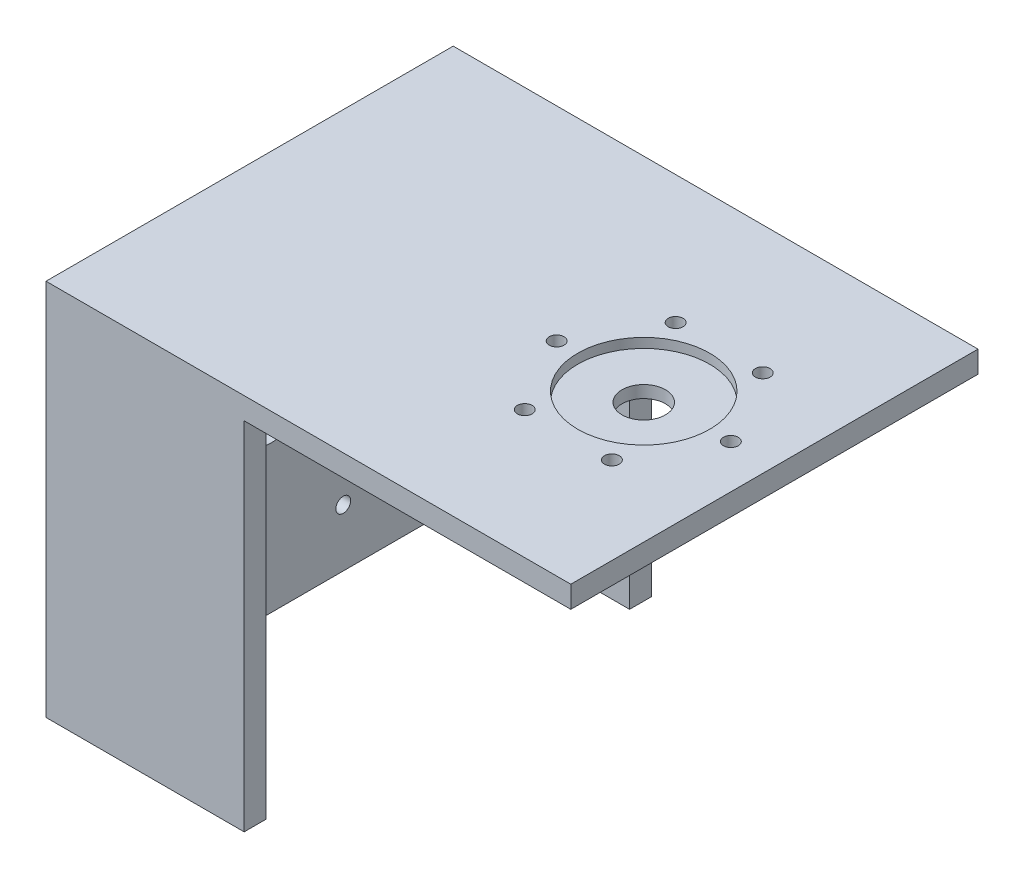
SolidWorks part; units mm, degrees
material "6061-T6 (SS)"
ref_plane "Front Plane" through (0, 0, 0) normal (0, 0, 1) x (1, 0, 0)
ref_plane "Top Plane" through (0, 0, 0) normal (0, 1, 0) x (1, 0, 0)
ref_plane "Right Plane" through (0, 0, 0) normal (1, 0, 0) x (0, 0, -1)
ref_plane "PL_Output_Plate_base" through (0, -5, 0) normal (0, 1, 0) x (1, 0, 0)
sketch "SK_Output_Plate" plane through (0, -5, 0) normal (0, 1, 0) x (1, 0, 0)
  line L0 (-90.5, 46.75) -> (30, 46.75)
  line L1 (30, 46.75) -> (30, -46.75)
  line L2 (30, -46.75) -> (-90.5, -46.75)
  line L3 (-90.5, -46.75) -> (-90.5, 46.75)
  circle A0 centre (20, 0) radius 1.7
  circle A1 centre (10, 17.3205) radius 1.7
  circle A2 centre (-10, 17.3205) radius 1.7
  circle A3 centre (-20, 0) radius 1.7
  circle A4 centre (-10, -17.3205) radius 1.7
  circle A5 centre (10, -17.3205) radius 1.7
  circle A6 centre (0, 0) radius 5
  dimension "D9_SK_Output_Plate" = 3.4
  dimension "D11_SK_Output_Plate" = 3.4
  dimension "D14_SK_Output_Plate" = 3.4
  dimension "D17_SK_Output_Plate" = 3.4
  dimension "D19_SK_Output_Plate" = 3.4
  dimension "D22_SK_Output_Plate" = 3.4
  dimension "D25_SK_Output_Plate" = 10
  dimension "P1" = 90.5
  dimension "P2" = 46.75
  dimension "P3" = 30
  dimension "P4" = 46.75
  dimension "P5" = 30
  dimension "P6" = 46.75
  dimension "P7" = 90.5
  dimension "P8" = 46.75
  dimension "P10" = 20
  dimension "P12" = 10
  dimension "P13" = 17.3205
  dimension "P15" = 10
  dimension "P16" = 17.3205
  dimension "P18" = 20
  dimension "P20" = 10
  dimension "P21" = 17.3205
  dimension "P23" = 10
  dimension "P24" = 17.3205
extrude "Output_Plate" add sketch "SK_Output_Plate" along normal blind 5
sketch "SK_Pitch_Pilot_Recess" plane through (0, 0, 0) normal (0, 1, 0) x (1, 0, 0)
  circle A0 centre (0, 0) radius 15.15
  dimension "D1_SK_Pitch_Pilot_Recess" = 30.3
extrude "Pitch_Pilot_Recess" cut sketch "SK_Pitch_Pilot_Recess" against normal blind 2.2
ref_plane "PL_Rear_Plate_base" through (-90.5, 0, 0) normal (1, 0, 0) x (0, 0, -1)
sketch "SK_Rear_Plate" plane through (-90.5, 0, 0) normal (1, 0, 0) x (0, 0, -1)
  line L0 (46.75, 0) -> (46.75, -86.75)
  line L1 (46.75, -86.75) -> (-46.75, -86.75)
  line L2 (-46.75, -86.75) -> (-46.75, 0)
  line L3 (-46.75, 0) -> (46.75, 0)
  circle A0 centre (0, -45) radius 8
  circle A1 centre (33, -45) radius 1.7
  circle A2 centre (16.5, -73.5788) radius 1.7
  circle A3 centre (-16.5, -73.5788) radius 1.7
  circle A4 centre (-33, -45) radius 1.7
  circle A5 centre (-16.5, -16.4212) radius 1.7
  circle A6 centre (16.5, -16.4212) radius 1.7
  dimension "D7_SK_Rear_Plate" = 16
  dimension "D9_SK_Rear_Plate" = 3.4
  dimension "D12_SK_Rear_Plate" = 3.4
  dimension "D15_SK_Rear_Plate" = 3.4
  dimension "D18_SK_Rear_Plate" = 3.4
  dimension "D21_SK_Rear_Plate" = 3.4
  dimension "D24_SK_Rear_Plate" = 3.4
  dimension "P1" = 46.75
  dimension "P2" = 46.75
  dimension "P3" = 86.75
  dimension "P4" = 46.75
  dimension "P5" = 86.75
  dimension "P6" = 46.75
  dimension "P8" = 45
  dimension "P10" = 33
  dimension "P11" = 45
  dimension "P13" = 16.5
  dimension "P14" = 73.5788
  dimension "P16" = 16.5
  dimension "P17" = 73.5788
  dimension "P19" = 33
  dimension "P20" = 45
  dimension "P22" = 16.5
  dimension "P23" = 16.4212
  dimension "P25" = 16.5
  dimension "P26" = 16.4212
extrude "Rear_Plate" add sketch "SK_Rear_Plate" along normal blind 5
ref_plane "PL_Top_Plate_base" through (0, 0, 41.75) normal (0, 0, 1) x (1, 0, 0)
sketch "SK_Top_Plate" plane through (0, 0, 41.75) normal (0, 0, 1) x (1, 0, 0)
  line L0 (-90.5, 0) -> (-45, 0)
  line L1 (-45, 0) -> (-45, -86.75)
  line L2 (-45, -86.75) -> (-90.5, -86.75)
  line L3 (-90.5, -86.75) -> (-90.5, 0)
  dimension "P1" = 90.5
  dimension "P2" = 45
  dimension "P3" = 45
  dimension "P4" = 86.75
  dimension "P5" = 90.5
  dimension "P6" = 86.75
extrude "Top_Plate" add sketch "SK_Top_Plate" along normal blind 5
ref_plane "PL_Bottom_Plate_base" through (0, 0, -46.75) normal (0, 0, 1) x (1, 0, 0)
sketch "SK_Bottom_Plate" plane through (0, 0, -46.75) normal (0, 0, 1) x (1, 0, 0)
  line L0 (-90.5, 0) -> (-45, 0)
  line L1 (-45, 0) -> (-45, -86.75)
  line L2 (-45, -86.75) -> (-90.5, -86.75)
  line L3 (-90.5, -86.75) -> (-90.5, 0)
  dimension "P1" = 90.5
  dimension "P2" = 45
  dimension "P3" = 45
  dimension "P4" = 86.75
  dimension "P5" = 90.5
  dimension "P6" = 86.75
extrude "Bottom_Plate" add sketch "SK_Bottom_Plate" along normal blind 5
equation "\"Roll_axis_y\"= 45"
equation "\"Roll_rear_x\"= -85.5"
